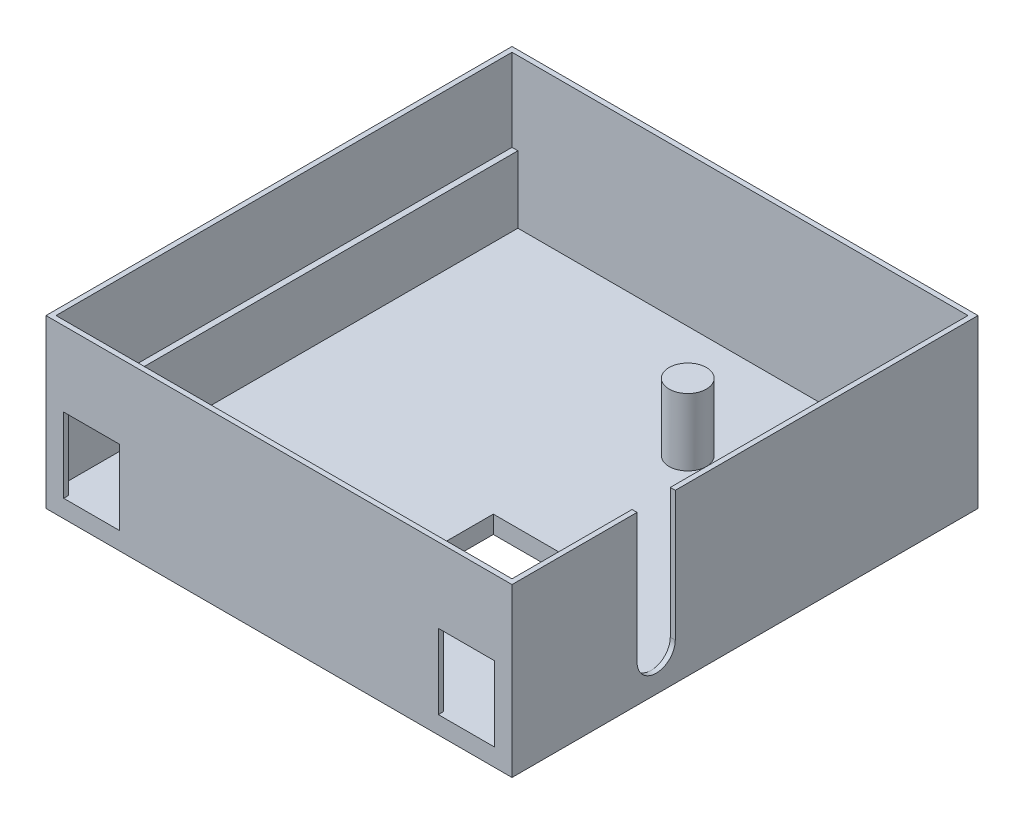
SolidWorks part; units mm, degrees
ref_plane "Front Plane" through (0, 0, 0) normal (0, 0, 1) x (1, 0, 0)
ref_plane "Top Plane" through (0, 0, 0) normal (0, 1, 0) x (1, 0, 0)
ref_plane "Right Plane" through (0, 0, 0) normal (1, 0, 0) x (0, 0, -1)
sketch "Sketch1" plane through (0, 0, 0) normal (0, 1, 0) x (1, 0, 0)
  line L1 (-39.6, -39.6) -> (39.6, -39.6)
  line L2 (-39.6, -39.6) -> (-39.6, 39.6)
  line L3 (-39.6, 39.6) -> (39.6, 39.6)
  line L4 (39.6, -39.6) -> (39.6, 39.6)
  line L5 (-39.6, -39.6) -> (39.6, 39.6) construction
  line L6 (-39.6, 39.6) -> (39.6, -39.6) construction
  point P0 (0, 0)
  dimension "D1" = 79.2
  dimension "D2" = 79.2
extrude "Boss-Extrude1" add sketch "Sketch1" along normal blind 3
sketch "Sketch2" plane through (0, 3, 0) normal (0, 1, 0) x (1, 0, 0)
  line L1 (-39.6, -39.6) -> (39.6, -39.6)
  line L2 (-39.6, -39.6) -> (-39.6, 39.6)
  line L3 (-39.6, 39.6) -> (39.6, 39.6)
  line L4 (39.6, -39.6) -> (39.6, 39.6)
  line L5 (-39.6, -39.6) -> (39.6, 39.6) construction
  line L6 (-39.6, 39.6) -> (39.6, -39.6) construction
  line L7 (-38.75, -38.75) -> (38.75, -38.75)
  line L8 (-38.75, -38.75) -> (-38.75, 38.75)
  line L9 (-38.75, 38.75) -> (38.75, 38.75)
  line L10 (38.75, -38.75) -> (38.75, 38.75)
  line L11 (-38.75, -38.75) -> (38.75, 38.75) construction
  line L12 (-38.75, 38.75) -> (38.75, -38.75) construction
  point P0 (0, 0)
  point P7 (0, 0)
  dimension "D1" = 77.5
  dimension "D2" = 77.5
extrude "Boss-Extrude2" add sketch "Sketch2" along normal blind 25.4
sketch "Sketch3" plane through (39.6, 0, 0) normal (1, 0, 0) x (0, 0, -1)
  line L0 (-39.6, 28.4) -> (-39.6, 0) construction
  line L1 (-39.6, 0) -> (39.6, 0) construction
  line L2 (-11.85, 6.35) -> (-11.85, 28.4)
  line L3 (-39.6, 28.4) -> (39.6, 28.4) construction
  line L4 (-11.85, 28.4) -> (-18.35, 28.4)
  line L5 (-18.35, 28.4) -> (-18.35, 6.35)
  circle A0 centre (-15.1, 6.35) radius 3.25
  line M3 (39.6, 28.4) -> (-39.6, 28.4)
  dimension "D3" = 6.5
  dimension "D1" = 24.5
  dimension "D2" = 6.35
extrude "Cut-Extrude2" cut sketch "Sketch3" against normal up to surface (0.85 mm away) contours A0 | A0 L2 L5 M3 up to face at (38.75, 15.7, 0)
sketch "Sketch5" plane through (0, 0, 39.6) normal (0, 0, 1) x (1, 0, 0)
  line L0 (39.6, 28.4) -> (39.6, 0) construction
  line L1 (27.075, 3) -> (36.6, 3)
  line L2 (27.075, 3) -> (27.075, 15.7)
  line L3 (27.075, 15.7) -> (36.6, 15.7)
  line L4 (36.6, 3) -> (36.6, 15.7)
  line L5 (27.075, 3) -> (36.6, 15.7) construction
  line L6 (27.075, 15.7) -> (36.6, 3) construction
  line L7 (-39.6, 0) -> (39.6, 0) construction
  line L8 (-39.6, 28.4) -> (-39.6, 0) construction
  line L9 (-36.6, 15.7) -> (-27.075, 15.7)
  line L10 (-36.6, 15.7) -> (-36.6, 3)
  line L11 (-36.6, 3) -> (-27.075, 3)
  line L12 (-27.075, 15.7) -> (-27.075, 3)
  line L13 (-36.6, 15.7) -> (-27.075, 3) construction
  line L14 (-36.6, 3) -> (-27.075, 15.7) construction
  point P0 (31.8375, 9.35)
  point P9 (-31.8375, 9.35)
  dimension "D1" = 12.7
  dimension "D2" = 9.525
  dimension "D3" = 3
  dimension "D4" = 3
  dimension "D5" = 12.7
  dimension "D6" = 9.525
  dimension "D7" = 3
  dimension "D8" = 3
extrude "Cut-Extrude3" cut sketch "Sketch5" against normal blind 19.05
sketch "Sketch6" plane through (0, 3, 0) normal (0, 1, 0) x (1, 0, 0)
  line L0 (38.75, -38.75) -> (38.75, 38.75) construction
  line L1 (38.75, 38.75) -> (-38.75, 38.75) construction
  line L3 (-38.75, 38.75) -> (-37.75, 38.75)
  line L4 (-38.75, 38.75) -> (-38.75, -26.25)
  line L5 (-38.75, -26.25) -> (-37.75, -26.25)
  line L6 (-37.75, 38.75) -> (-37.75, -26.25)
  circle A0 centre (10.175, 19.7) radius 3.175
  point P13 (0, 0)
  dimension "D3" = 6.35
  dimension "D1" = 28.575
  dimension "D2" = 19.05
  dimension "D4" = 1
  dimension "D5" = 65
extrude "Boss-Extrude3" add sketch "Sketch6" along normal blind 11.4
sketch "Sketch7" plane through (0, 3, 0) normal (0, 1, 0) x (1, 0, 0)
  line L0 (-38.75, -38.75) -> (-36.6, -38.75) construction
  line L1 (2.2375, -18.1125) -> (14.9375, -18.1125)
  line L2 (2.2375, -18.1125) -> (2.2375, -5.4125)
  line L3 (2.2375, -5.4125) -> (14.9375, -5.4125)
  line L4 (14.9375, -18.1125) -> (14.9375, -5.4125)
  line L5 (2.2375, -18.1125) -> (14.9375, -5.4125) construction
  line L6 (2.2375, -5.4125) -> (14.9375, -18.1125) construction
  line L7 (38.75, -38.75) -> (38.75, 38.75) construction
  point P0 (8.5875, -11.7625)
  dimension "D1" = 12.7
  dimension "D2" = 12.7
  dimension "D3" = 26.9875
  dimension "D4" = 30.1625
extrude "Cut-Extrude5" cut sketch "Sketch7" against normal blind 26
